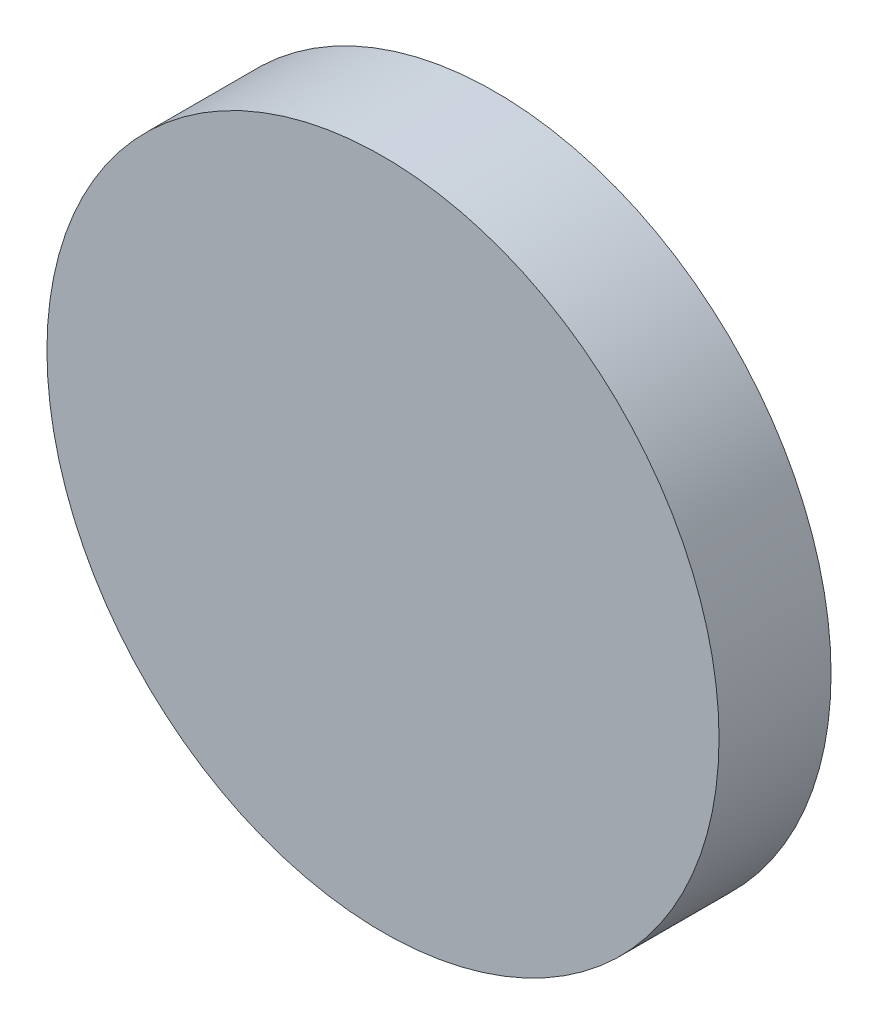
SolidWorks part; units mm, degrees
ref_plane "Front Plane" through (0, 0, 0) normal (0, 0, 1) x (1, 0, 0)
ref_plane "Top Plane" through (0, 0, 0) normal (0, 1, 0) x (1, 0, 0)
ref_plane "Right Plane" through (0, 0, 0) normal (1, 0, 0) x (0, 0, -1)
sketch "Sketch1" plane through (0, 0, 0) normal (0, 0, 1) x (1, 0, 0)
  circle A0 centre (0, 0) radius 10
extrude "Boss-Extrude1" add sketch "Sketch1" along normal blind 12 contours A0
sketch "Sketch3" plane through (0, 0, 0) normal (0, 1, 0) x (1, 0, 0)
  line L0 (0, -9) -> (0, 291)
  arc A0 (0, -9) -> (0, 291) centre (0, 141) cw
  point P4 (0, 0)
revolve "Cut-Revolve1" cut sketch "Sketch3" angle 360 about L0
